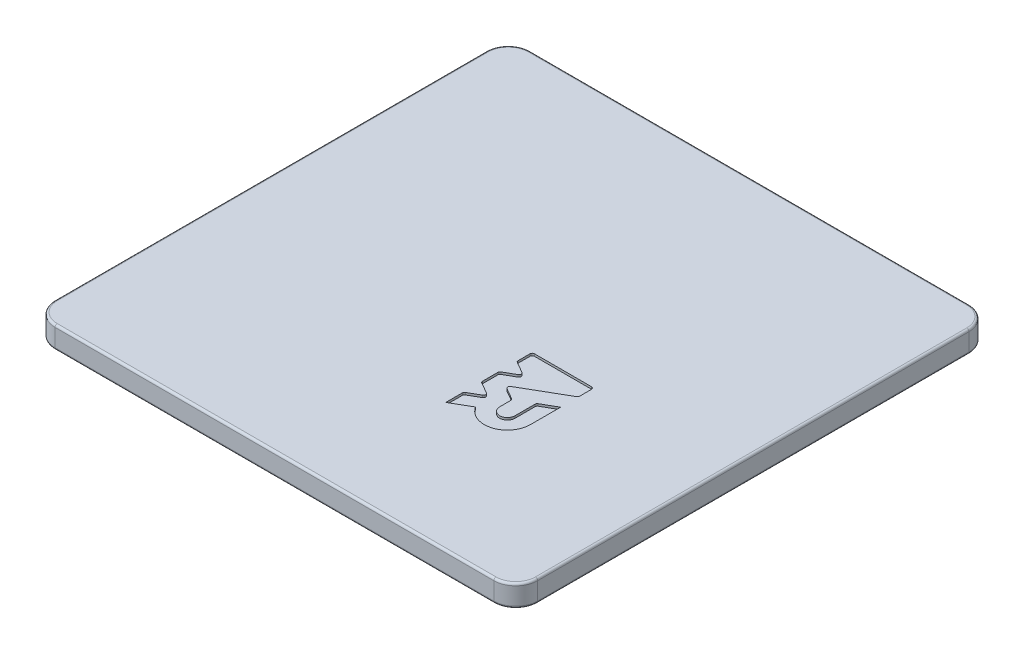
SolidWorks part; units mm, degrees
ref_plane "Front Plane" through (0, 0, 0) normal (0, 0, 1) x (1, 0, 0)
ref_plane "Top Plane" through (0, 0, 0) normal (0, 1, 0) x (1, 0, 0)
ref_plane "Right Plane" through (0, 0, 0) normal (1, 0, 0) x (0, 0, -1)
sketch "Sketch1" plane through (0, 0, 0) normal (0, 1, 0) x (1, 0, 0)
  line L0 (-123.3595, 77.7297) -> (96.2581, 77.7297)
  line L1 (-123.3595, 77.7297) -> (-123.3595, -138.4809)
  line L2 (96.2581, 77.7297) -> (96.2581, -138.4809)
  line L3 (-123.3595, -138.4809) -> (96.2581, -138.4809)
extrude "Boss-Extrude1" add sketch "Sketch1" along normal blind 10
sketch "Sketch2" plane through (0, 10, 0) normal (0, 1, 0) x (1, 0, 0)
  line L8 (34.1009, -40.8192) -> (6.1009, -40.8192) construction
  line L11 (34.1009, -40.8192) -> (34.1009, -80.1508) construction
  line L12 (6.1009, -40.8192) -> (6.1009, -80.1508) construction
  line L13 (34.1009, -80.1508) -> (6.1009, -80.1508) construction
  line L14 (34.1009, -40.8192) -> (34.1009, -47.2418)
  line L15 (34.1009, -40.8192) -> (6.1009, -40.8192)
  line L16 (34.1009, -47.8192) -> (6.1009, -47.8192) construction
  line L17 (6.1009, -40.8192) -> (6.1009, -47.2418)
  line L18 (34.1009, -55.9021) -> (27.6009, -59.6548)
  line L19 (33.6009, -48.1078) -> (20.1009, -55.9021)
  line L26 (20.1009, -55.9021) -> (6.6009, -48.1078)
  line L36 (20.1009, -63.985) -> (6.6009, -71.7792)
  line L37 (34.1009, -55.9021) -> (34.1009, -69.6508)
  line L38 (6.1009, -72.6452) -> (6.1009, -80.1508)
  line L39 (6.1009, -80.1508) -> (13.1009, -76.1093)
  line L40 (13.1009, -76.1093) -> (13.1009, -69.6508)
  line L41 (27.1009, -60.5209) -> (27.1009, -69.6508)
  line L42 (34.1009, -69.6508) -> (13.1009, -69.6508) construction
  line L43 (20.1009, -63.985) -> (20.1009, -69.6508)
  line L44 (27.1009, -69.6508) -> (20.1009, -69.6508) construction
  line L46 (13.1009, -51.8606) -> (6.6009, -55.6134)
  line L47 (6.1009, -56.4794) -> (6.1009, -63.4076)
  line L48 (20.1009, -55.9021) -> (13.1009, -59.9435)
  line L49 (13.1009, -59.9435) -> (20.1009, -63.985)
  line L50 (34.1009, -80.1508) -> (6.1009, -80.1508) construction
  line L51 (6.6009, -64.2736) -> (13.1009, -68.0264)
  line L52 (13.1009, -76.1093) -> (14.6842, -75.1953)
  arc A0 (34.1009, -69.6508) -> (13.1009, -69.6508) centre (23.6009, -69.6508) cw
  arc A1 (27.1009, -69.6508) -> (20.1009, -69.6508) centre (23.6009, -69.6508) cw
  arc A2 (27.6009, -59.6548) -> (27.1009, -60.5209) centre (28.1009, -60.5209) ccw
  arc A7 (34.1009, -47.2418) -> (33.6009, -48.1078) centre (33.1009, -47.2418) cw
  arc A8 (6.6009, -48.1078) -> (6.1009, -47.2418) centre (7.1009, -47.2418) cw
  arc A9 (6.1009, -63.4076) -> (6.6009, -64.2736) centre (7.1009, -63.4076) ccw
  arc A10 (6.6009, -55.6134) -> (6.1009, -56.4794) centre (7.1009, -56.4794) ccw
  arc A11 (6.6009, -71.7792) -> (6.1009, -72.6452) centre (7.1009, -72.6452) ccw
  point P36 (6.1009, -72.0679)
  dimension "D8" = 7
  dimension "D6" = 1
  dimension "D10" = 1
  dimension "D1" = 30
  dimension "D2" = 30
  dimension "D3" = 7
  dimension "D4" = 30
  dimension "D5" = 7
  dimension "D7" = 7
  dimension "D9" = 7
  dimension "D11" = 10.5
extrude "Cut-Extrude1" cut sketch "Sketch2" against normal blind 1
fillet "Fillet3" radius 10 4 edges at (96.2581, 5, -77.7297) (-123.3595, 5, -77.7297) (-123.3595, 5, 138.4809) (96.2581, 5, 138.4809)
fillet "Fillet4" radius 1 22 edges at (96.2581, 0, 30.3756) (-13.5507, 0, -77.7297) (-123.3595, 0, 30.3756) (-13.5507, 0, 138.4809) (-13.5507, 10, 138.4809) (-123.3595, 10, 30.3756) (-13.5507, 10, -77.7297) (96.2581, 10, 30.3756) (93.3291, 0, -74.8008) (93.3291, 10, -74.8008) (-120.4305, 0, -74.8008) (-120.4305, 10, -74.8008) (-120.4305, 0, 135.552) (-120.4305, 10, 135.552) (93.3291, 0, 135.552) (93.3291, 10, 135.552) (34.1009, 9.5, 40.8192) (6.1009, 9.5, 40.8192) (13.1009, 9.5, 51.8606) (13.1009, 9.5, 68.0264) (20.1009, 9.5, 63.985) (13.1009, 9.5, 59.9435)
